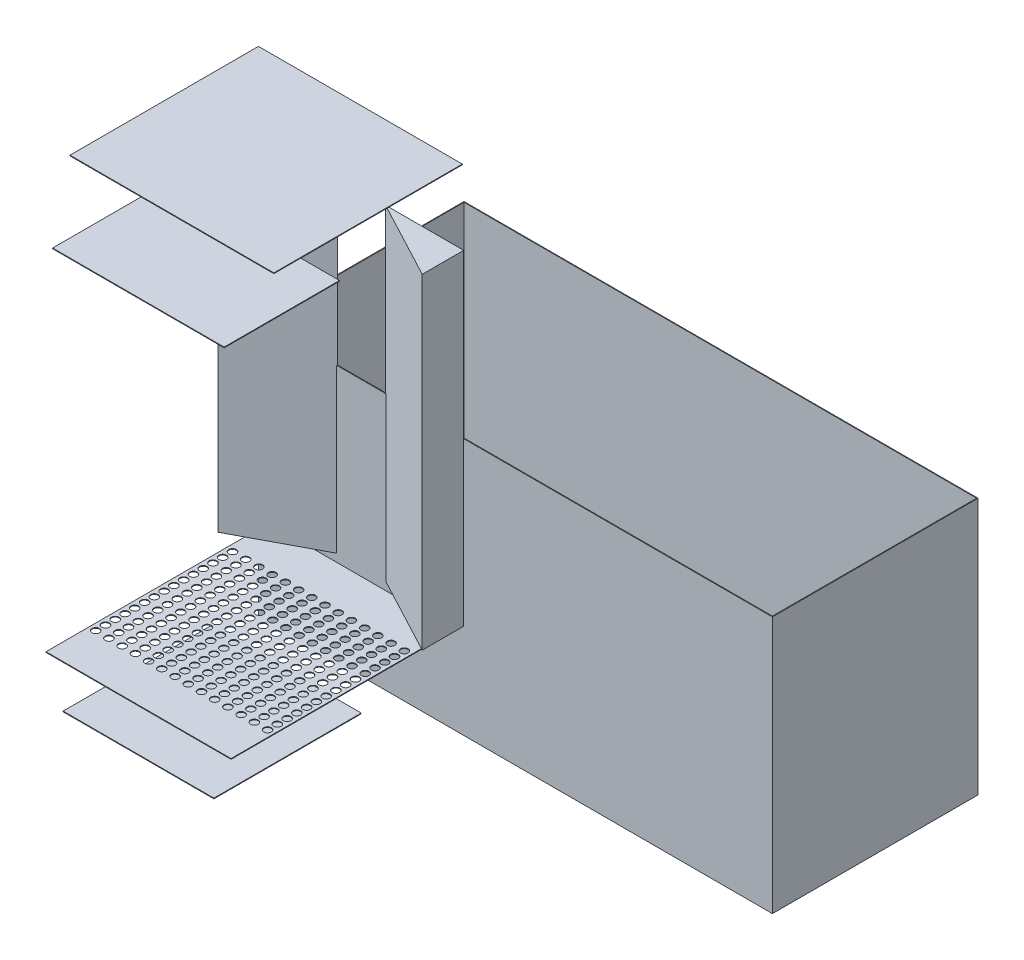
SolidWorks part; units mm, degrees
ref_plane "Спереди" through (0, 0, 0) normal (0, 0, 1) x (1, 0, 0)
ref_plane "Сверху" through (0, 0, 0) normal (0, 1, 0) x (1, 0, 0)
ref_plane "Справа" through (0, 0, 0) normal (1, 0, 0) x (0, 0, -1)
sketch "MASTER_FOOTPRINT" plane through (0, 0, 0) normal (0, 1, 0) x (1, 0, 0)
  line L1 (0, 0) -> (1500, 0)
  line L2 (0, 0) -> (0, 600)
  line L3 (0, 600) -> (1500, 600)
  line L4 (1500, 0) -> (1500, 600)
  dimension "D1" = 1500
  dimension "D2" = 600
extrude "BATH_BASE_PLATE" add sketch "MASTER_FOOTPRINT" along normal blind 750
shell "BATH_SHELL_2MM" thickness 2
sketch "Эскиз1" plane through (0, 0, 0) normal (0, 1, 0) x (1, 0, 0)
  line L1 (80, -220) -> (520, -220)
  line L2 (80, -220) -> (80, -650)
  line L3 (80, -650) -> (520, -650)
  line L4 (520, -220) -> (520, -650)
extrude "INLET_IMPACT_BAFFLE" add sketch "Эскиз1" along normal blind 2 from offset 125 separate body
sketch "Эскиз2" plane through (0, 0, 0) normal (0, 1, 0) x (1, 0, 0)
  line L0 (2, 2) -> (1498, 2) construction
  line L1 (30, 2) -> (570, 2)
  line L2 (30, 2) -> (30, -650)
  line L3 (30, -650) -> (570, -650)
  line L4 (570, 2) -> (570, -650)
  circle A0 centre (49.2857, -125) radius 11
  circle A1 centre (49.2857, -153.5) radius 11
  circle A2 centre (49.2857, -182) radius 11
  circle A3 centre (49.2857, -210.5) radius 11
  circle A4 centre (49.2857, -239) radius 11
  circle A5 centre (49.2857, -267.5) radius 11
  circle A6 centre (49.2857, -296) radius 11
  circle A7 centre (49.2857, -324.5) radius 11
  circle A8 centre (49.2857, -353) radius 11
  circle A9 centre (49.2857, -381.5) radius 11
  circle A10 centre (49.2857, -410) radius 11
  circle A11 centre (49.2857, -438.5) radius 11
  circle A12 centre (49.2857, -467) radius 11
  circle A13 centre (49.2857, -495.5) radius 11
  circle A14 centre (49.2857, -524) radius 11
  circle A15 centre (87.8571, -125) radius 11
  circle A16 centre (87.8571, -153.5) radius 11
  circle A17 centre (87.8571, -182) radius 11
  circle A18 centre (87.8571, -210.5) radius 11
  circle A19 centre (87.8571, -239) radius 11
  circle A20 centre (87.8571, -267.5) radius 11
  circle A21 centre (87.8571, -296) radius 11
  circle A22 centre (87.8571, -324.5) radius 11
  circle A23 centre (87.8571, -353) radius 11
  circle A24 centre (87.8571, -381.5) radius 11
  circle A25 centre (87.8571, -410) radius 11
  circle A26 centre (87.8571, -438.5) radius 11
  circle A27 centre (87.8571, -467) radius 11
  circle A28 centre (87.8571, -495.5) radius 11
  circle A29 centre (87.8571, -524) radius 11
  circle A30 centre (126.4286, -125) radius 11
  circle A31 centre (126.4286, -153.5) radius 11
  circle A32 centre (126.4286, -182) radius 11
  circle A33 centre (126.4286, -210.5) radius 11
  circle A34 centre (126.4286, -239) radius 11
  circle A35 centre (126.4286, -267.5) radius 11
  circle A36 centre (126.4286, -296) radius 11
  circle A37 centre (126.4286, -324.5) radius 11
  circle A38 centre (126.4286, -353) radius 11
  circle A39 centre (126.4286, -381.5) radius 11
  circle A40 centre (126.4286, -410) radius 11
  circle A41 centre (126.4286, -438.5) radius 11
  circle A42 centre (126.4286, -467) radius 11
  circle A43 centre (126.4286, -495.5) radius 11
  circle A44 centre (126.4286, -524) radius 11
  circle A45 centre (165, -125) radius 11
  circle A46 centre (165, -153.5) radius 11
  circle A47 centre (165, -182) radius 11
  circle A48 centre (165, -210.5) radius 11
  circle A49 centre (165, -239) radius 11
  circle A50 centre (165, -267.5) radius 11
  circle A51 centre (165, -296) radius 11
  circle A52 centre (165, -324.5) radius 11
  circle A53 centre (165, -353) radius 11
  circle A54 centre (165, -381.5) radius 11
  circle A55 centre (165, -410) radius 11
  circle A56 centre (165, -438.5) radius 11
  circle A57 centre (165, -467) radius 11
  circle A58 centre (165, -495.5) radius 11
  circle A59 centre (165, -524) radius 11
  circle A60 centre (203.5714, -125) radius 11
  circle A61 centre (203.5714, -153.5) radius 11
  circle A62 centre (203.5714, -182) radius 11
  circle A63 centre (203.5714, -210.5) radius 11
  circle A64 centre (203.5714, -239) radius 11
  circle A65 centre (203.5714, -267.5) radius 11
  circle A66 centre (203.5714, -296) radius 11
  circle A67 centre (203.5714, -324.5) radius 11
  circle A68 centre (203.5714, -353) radius 11
  circle A69 centre (203.5714, -381.5) radius 11
  circle A70 centre (203.5714, -410) radius 11
  circle A71 centre (203.5714, -438.5) radius 11
  circle A72 centre (203.5714, -467) radius 11
  circle A73 centre (203.5714, -495.5) radius 11
  circle A74 centre (203.5714, -524) radius 11
  circle A75 centre (242.1429, -125) radius 11
  circle A76 centre (242.1429, -153.5) radius 11
  circle A77 centre (242.1429, -182) radius 11
  circle A78 centre (242.1429, -210.5) radius 11
  circle A79 centre (242.1429, -239) radius 11
  circle A80 centre (242.1429, -267.5) radius 11
  circle A81 centre (242.1429, -296) radius 11
  circle A82 centre (242.1429, -324.5) radius 11
  circle A83 centre (242.1429, -353) radius 11
  circle A84 centre (242.1429, -381.5) radius 11
  circle A85 centre (242.1429, -410) radius 11
  circle A86 centre (242.1429, -438.5) radius 11
  circle A87 centre (242.1429, -467) radius 11
  circle A88 centre (242.1429, -495.5) radius 11
  circle A89 centre (242.1429, -524) radius 11
  circle A90 centre (280.7143, -125) radius 11
  circle A91 centre (280.7143, -153.5) radius 11
  circle A92 centre (280.7143, -182) radius 11
  circle A93 centre (280.7143, -210.5) radius 11
  circle A94 centre (280.7143, -239) radius 11
  circle A95 centre (280.7143, -267.5) radius 11
  circle A96 centre (280.7143, -296) radius 11
  circle A97 centre (280.7143, -324.5) radius 11
  circle A98 centre (280.7143, -353) radius 11
  circle A99 centre (280.7143, -381.5) radius 11
  circle A100 centre (280.7143, -410) radius 11
  circle A101 centre (280.7143, -438.5) radius 11
  circle A102 centre (280.7143, -467) radius 11
  circle A103 centre (280.7143, -495.5) radius 11
  circle A104 centre (280.7143, -524) radius 11
  circle A105 centre (319.2857, -125) radius 11
  circle A106 centre (319.2857, -153.5) radius 11
  circle A107 centre (319.2857, -182) radius 11
  circle A108 centre (319.2857, -210.5) radius 11
  circle A109 centre (319.2857, -239) radius 11
  circle A110 centre (319.2857, -267.5) radius 11
  circle A111 centre (319.2857, -296) radius 11
  circle A112 centre (319.2857, -324.5) radius 11
  circle A113 centre (319.2857, -353) radius 11
  circle A114 centre (319.2857, -381.5) radius 11
  circle A115 centre (319.2857, -410) radius 11
  circle A116 centre (319.2857, -438.5) radius 11
  circle A117 centre (319.2857, -467) radius 11
  circle A118 centre (319.2857, -495.5) radius 11
  circle A119 centre (319.2857, -524) radius 11
  circle A120 centre (357.8571, -125) radius 11
  circle A121 centre (357.8571, -153.5) radius 11
  circle A122 centre (357.8571, -182) radius 11
  circle A123 centre (357.8571, -210.5) radius 11
  circle A124 centre (357.8571, -239) radius 11
  circle A125 centre (357.8571, -267.5) radius 11
  circle A126 centre (357.8571, -296) radius 11
  circle A127 centre (357.8571, -324.5) radius 11
  circle A128 centre (357.8571, -353) radius 11
  circle A129 centre (357.8571, -381.5) radius 11
  circle A130 centre (357.8571, -410) radius 11
  circle A131 centre (357.8571, -438.5) radius 11
  circle A132 centre (357.8571, -467) radius 11
  circle A133 centre (357.8571, -495.5) radius 11
  circle A134 centre (357.8571, -524) radius 11
  circle A135 centre (396.4286, -125) radius 11
  circle A136 centre (396.4286, -153.5) radius 11
  circle A137 centre (396.4286, -182) radius 11
  circle A138 centre (396.4286, -210.5) radius 11
  circle A139 centre (396.4286, -239) radius 11
  circle A140 centre (396.4286, -267.5) radius 11
  circle A141 centre (396.4286, -296) radius 11
  circle A142 centre (396.4286, -324.5) radius 11
  circle A143 centre (396.4286, -353) radius 11
  circle A144 centre (396.4286, -381.5) radius 11
  circle A145 centre (396.4286, -410) radius 11
  circle A146 centre (396.4286, -438.5) radius 11
  circle A147 centre (396.4286, -467) radius 11
  circle A148 centre (396.4286, -495.5) radius 11
  circle A149 centre (396.4286, -524) radius 11
  circle A150 centre (435, -125) radius 11
  circle A151 centre (435, -153.5) radius 11
  circle A152 centre (435, -182) radius 11
  circle A153 centre (435, -210.5) radius 11
  circle A154 centre (435, -239) radius 11
  circle A155 centre (435, -267.5) radius 11
  circle A156 centre (435, -296) radius 11
  circle A157 centre (435, -324.5) radius 11
  circle A158 centre (435, -353) radius 11
  circle A159 centre (435, -381.5) radius 11
  circle A160 centre (435, -410) radius 11
  circle A161 centre (435, -438.5) radius 11
  circle A162 centre (435, -467) radius 11
  circle A163 centre (435, -495.5) radius 11
  circle A164 centre (435, -524) radius 11
  circle A165 centre (473.5714, -125) radius 11
  circle A166 centre (473.5714, -153.5) radius 11
  circle A167 centre (473.5714, -182) radius 11
  circle A168 centre (473.5714, -210.5) radius 11
  circle A169 centre (473.5714, -239) radius 11
  circle A170 centre (473.5714, -267.5) radius 11
  circle A171 centre (473.5714, -296) radius 11
  circle A172 centre (473.5714, -324.5) radius 11
  circle A173 centre (473.5714, -353) radius 11
  circle A174 centre (473.5714, -381.5) radius 11
  circle A175 centre (473.5714, -410) radius 11
  circle A176 centre (473.5714, -438.5) radius 11
  circle A177 centre (473.5714, -467) radius 11
  circle A178 centre (473.5714, -495.5) radius 11
  circle A179 centre (473.5714, -524) radius 11
  circle A180 centre (512.1429, -125) radius 11
  circle A181 centre (512.1429, -153.5) radius 11
  circle A182 centre (512.1429, -182) radius 11
  circle A183 centre (512.1429, -210.5) radius 11
  circle A184 centre (512.1429, -239) radius 11
  circle A185 centre (512.1429, -267.5) radius 11
  circle A186 centre (512.1429, -296) radius 11
  circle A187 centre (512.1429, -324.5) radius 11
  circle A188 centre (512.1429, -353) radius 11
  circle A189 centre (512.1429, -381.5) radius 11
  circle A190 centre (512.1429, -410) radius 11
  circle A191 centre (512.1429, -438.5) radius 11
  circle A192 centre (512.1429, -467) radius 11
  circle A193 centre (512.1429, -495.5) radius 11
  circle A194 centre (512.1429, -524) radius 11
  circle A195 centre (550.7143, -125) radius 11
  circle A196 centre (550.7143, -153.5) radius 11
  circle A197 centre (550.7143, -182) radius 11
  circle A198 centre (550.7143, -210.5) radius 11
  circle A199 centre (550.7143, -239) radius 11
  circle A200 centre (550.7143, -267.5) radius 11
  circle A201 centre (550.7143, -296) radius 11
  circle A202 centre (550.7143, -324.5) radius 11
  circle A203 centre (550.7143, -353) radius 11
  circle A204 centre (550.7143, -381.5) radius 11
  circle A205 centre (550.7143, -410) radius 11
  circle A206 centre (550.7143, -438.5) radius 11
  circle A207 centre (550.7143, -467) radius 11
  circle A208 centre (550.7143, -495.5) radius 11
  circle A209 centre (550.7143, -524) radius 11
extrude "DISTRIBUTOR_D22" add sketch "Эскиз2" along normal blind 2 from offset 250 separate body
sketch "Эскиз3" plane through (0, 0, 0) normal (0, 1, 0) x (1, 0, 0)
  line L0 (30, -650) -> (570, -650) construction
  line L1 (49.2857, -313.5) -> (550, -313.5)
  line L2 (49.2857, -313.5) -> (49.2857, -650)
  line L3 (49.2857, -650) -> (550, -650)
  line L4 (550, -313.5) -> (550, -650)
  circle A0 centre (49.2857, -324.5) radius 11 construction
extrude "OUTLET_SUBMERGED_BAFFLE" add sketch "Эскиз3" along normal blind 2 from offset 1280 separate body
sketch "Эскиз4" plane through (0, 0, 0) normal (0, 1, 0) x (1, 0, 0)
  line L1 (0, 0) -> (595, 0)
  line L2 (0, 0) -> (0, -550)
  line L3 (0, -550) -> (595, -550)
  line L4 (595, 0) -> (595, -550)
extrude "OVERFLOW_WEIR_Z550" add sketch "Эскиз4" along normal blind 2 from offset 1440 separate body
sketch "Эскиз5" plane through (0, 0, 0) normal (0, 1, 0) x (1, 0, 0)
  line L0 (2, 1) -> (2, -120)
  line L1 (2, -120) -> (230, 1)
  line L2 (230, 1) -> (2, 1)
  line L3 (598, 1) -> (598, -120)
  line L4 (598, -120) -> (370, 1)
  line L5 (370, 1) -> (598, 1)
extrude "SLOPED_SEDIMENT_FLOOR" add sketch "Эскиз5" along normal blind 950 from offset 275
equation "\"AI_Q_Peak\"= 0.006"
equation "\"AI_B_Bath\" = 600"
equation "\"AI_L_Settle\" = 1050"
equation "\"AI_L_Inlet\"= 250"
equation "\"AI_L_Outlet\"= 200"
equation "\"AI_L_Bath\" = 1500"
equation "\"AI_H_Water\"= 550"
equation "\"AI_H_Freeboard\"= 200"
equation "\"AI_H_Bath\"= 750"
equation "\"AI_Shell_Thickness\"= 2"
equation "\"AI_Inlet_DN\"= 100"
equation "\"AI_Weir_Width\"= 600"
equation "\"AI_Inlet_Baffle_Offset\"= 125"
equation "\"AI_Distributor_Open_Area\"= 0.28"
equation "\"AI_Distributor_Hole_Dia\"= 22"
equation "\"AI_Distributor_Blind_Zone\"= 110"
equation "\"AI_Outlet_Baffle_Depth\"= 250"
equation "\"AI_Screw_Diameter\"= 100"
equation "\"AI_Screw_Pitch\"= 100"
equation "\"AI_Screw_Angle\"= 30"
equation "\"AI_Screw_Rpm\"= 15"
equation "\"AI_Screw_Clearance\"= 5"
equation "\"AI_Liner_Thickness\"= 5"
equation "\"AI_Discharge_Height\"= 650"
equation "\"AI_Frame_Height\"= 500"
equation "\"D1@MASTER_FOOTPRINT\" = \"AI_L_Bath\""
equation "\"D2@MASTER_FOOTPRINT\" = \"AI_B_Bath\""
equation "\"D1@BATH_BASE_PLATE\" = \"AI_H_Bath\""
